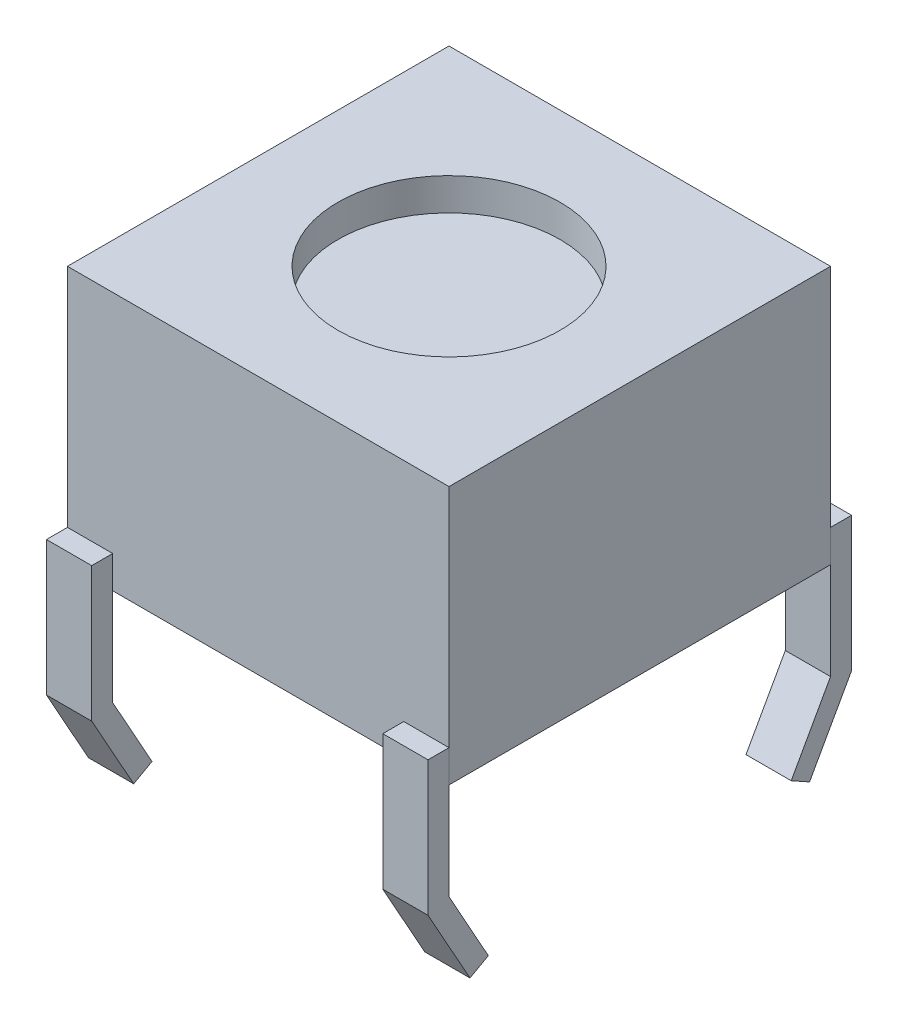
SolidWorks part; units mm, degrees
ref_plane "Front Plane" through (0, 0, 0) normal (0, 0, 1) x (1, 0, 0)
ref_plane "Top Plane" through (0, 0, 0) normal (0, 1, 0) x (1, 0, 0)
ref_plane "Right Plane" through (0, 0, 0) normal (1, 0, 0) x (0, 0, -1)
sketch "Sketch1" plane through (0, 0, 0) normal (0, 1, 0) x (1, 0, 0)
  line L1 (-3, 3) -> (3, 3)
  line L2 (-3, 3) -> (-3, -3)
  line L3 (-3, -3) -> (3, -3)
  line L4 (3, 3) -> (3, -3)
  line L5 (-3, 3) -> (3, -3) construction
  line L6 (-3, -3) -> (3, 3) construction
  point P0 (0, 0)
  dimension "D1" = 6
extrude "Boss-Extrude1" add sketch "Sketch1" along normal blind 4.064
sketch "Sketch2" plane through (3, 0, 0) normal (1, 0, 0) x (0, 0, -1)
  line L0 (-3, 0) -> (-3, -1.524)
  line L1 (-3, -1.524) -> (-2.3814, -2.6332)
  line L2 (-2.3814, -2.6332) -> (-2.6698, -2.794)
  line L3 (-2.6698, -2.794) -> (-3.3302, -1.6099)
  line L4 (-3.3302, -1.6099) -> (-3.3302, 0.508)
  line L5 (-3.3302, 0.508) -> (-3, 0.508)
  line L6 (-3, 4.064) -> (-3, 0) construction
  line L7 (-3, 0) -> (-3, 0.508)
  dimension "D1" = 1.524
  dimension "D2" = 1.27
  dimension "D3" = 0.3302
  dimension "D4" = 0.508
  dimension "D5" = 6.858
extrude "Boss-Extrude2" add sketch "Sketch2" against normal blind 0.7112
pattern_linear "LPattern1" count 2 spacing 5.2888 along (-1, 0, 0) of "Boss-Extrude2"
mirror "Mirror1" about plane through (0, 0, 0) normal (0, 0, 1) of "LPattern1", "Boss-Extrude2"
sketch "Sketch3" plane through (0, 4.064, 0) normal (0, 1, 0) x (1, 0, 0)
  circle A0 centre (0, 0) radius 1.7463
  dimension "D1" = 3.4925
extrude "Cut-Extrude1" cut sketch "Sketch3" against normal blind 0.508
sketch "Sketch4" plane through (-3, 0, 0) normal (-1, 0, 0) x (0, 0, 1)
  line L0 (3, 0.508) -> (3, 0)
  line L1 (-3, 0) -> (-3, 0.508)
split line "Split Line4"
